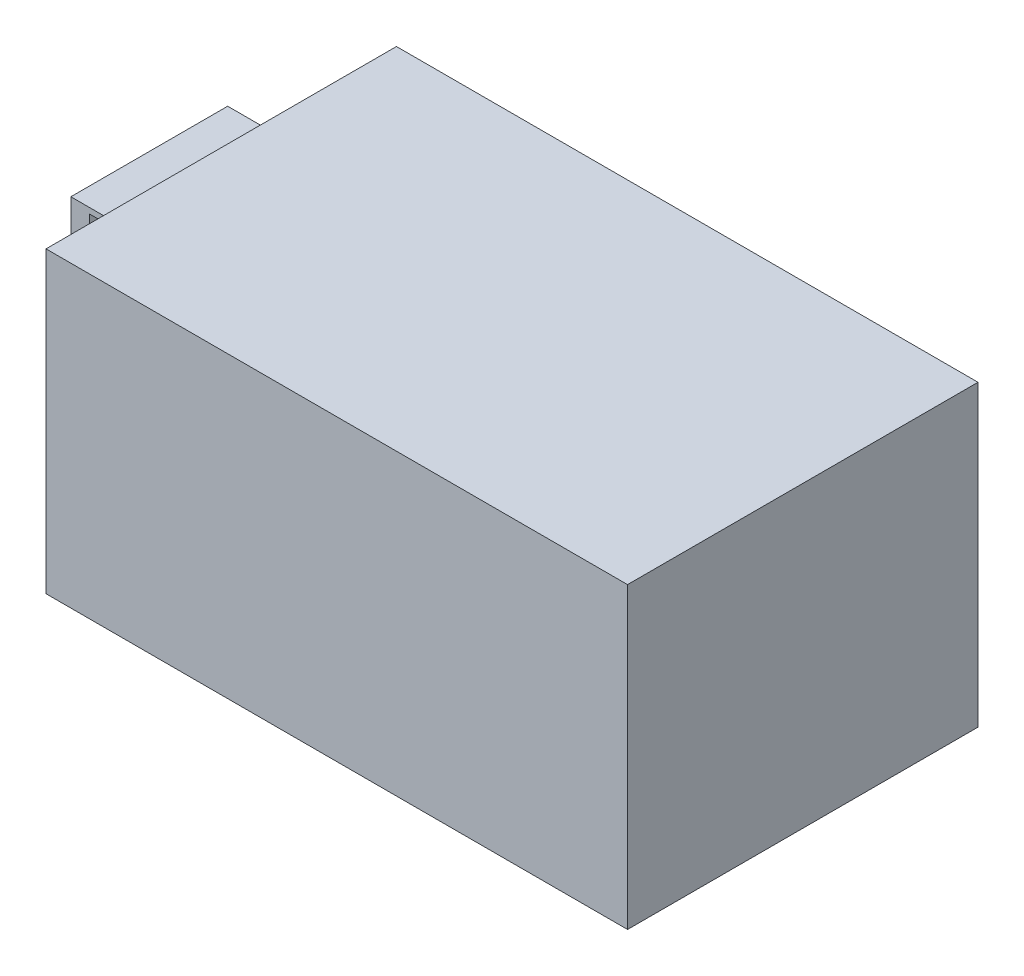
SolidWorks part; units mm, degrees
ref_plane "Front" through (0, 0, 0) normal (0, 0, 1) x (1, 0, 0)
ref_plane "Top" through (0, 0, 0) normal (0, 1, 0) x (1, 0, 0)
ref_plane "Right" through (0, 0, 0) normal (1, 0, 0) x (0, 0, -1)
sketch "Sketch1" plane through (0, 0, 0) normal (0, 1, 0) x (1, 0, 0)
  line L1 (-38.7115, 25.1796) -> (39.1683, 25.1796)
  line L2 (-38.7115, 25.1796) -> (-38.7115, -21.7538)
  line L3 (-38.7115, -21.7538) -> (39.1683, -21.7538)
  line L4 (39.1683, 25.1796) -> (39.1683, -21.7538)
extrude "Boss-Extrude1" add sketch "Sketch1" along normal blind 40
sketch "Sketch7" plane through (0, 0, 0) normal (0, 1, 0) x (1, 0, 0)
  line L1 (-53.0905, 16.955) -> (-15.0905, 16.955)
  line L2 (-53.0905, 16.955) -> (-53.0905, -4.045)
  line L3 (-53.0905, -4.045) -> (-15.0905, -4.045)
  line L4 (-15.0905, 16.955) -> (-15.0905, -4.045)
  dimension "D1" = 38
  dimension "D2" = 21
extrude "Boss-Extrude3" add sketch "Sketch7" along normal blind 30 separate body
sketch "Sketch8" plane through (0, 0, 4.045) normal (0, 0, 1) x (1, 0, 0)
  line L1 (-50.5905, 29.25) -> (-10.5905, 29.25)
  line L2 (-50.5905, 29.25) -> (-50.5905, 0.75)
  line L3 (-50.5905, 0.75) -> (-10.5905, 0.75)
  line L4 (-10.5905, 29.25) -> (-10.5905, 0.75)
  line L7 (50, 0) -> (-50, 0) construction
  point P7 (-51.0973, 30)
  dimension "D1" = 28.5
  dimension "D2" = 2.5
  dimension "D3" = 0.75
  dimension "D4" = 40
extrude "Cut-Extrude1" cut sketch "Sketch8" against normal blind 50
